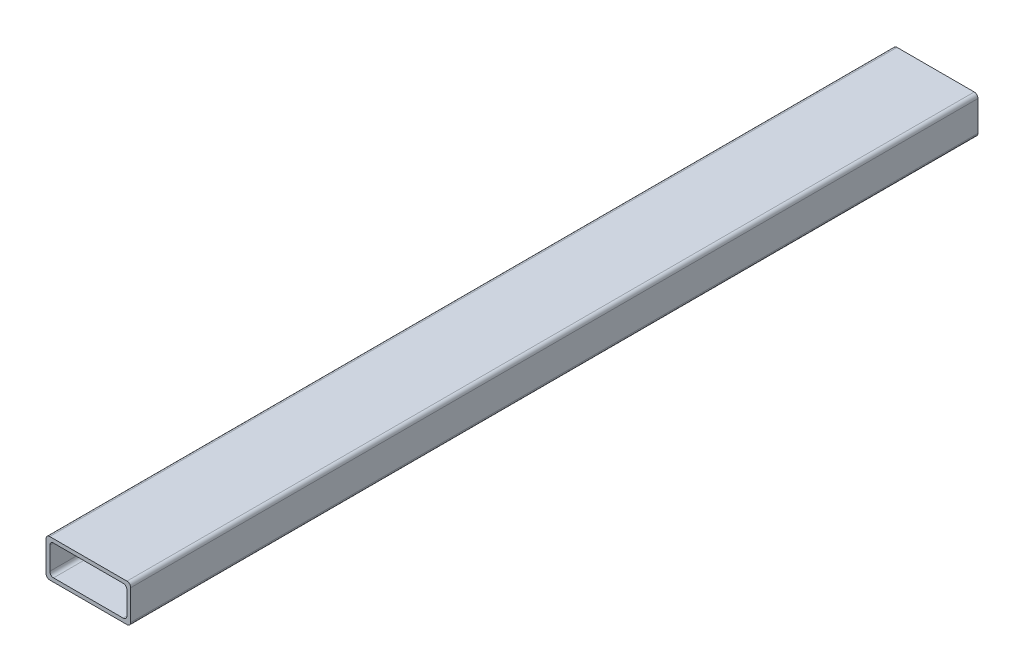
SolidWorks part; units mm, degrees
material "1.0490 (S275N)"
ref_plane "Front Plane" through (0, 0, 0) normal (0, 0, 1) x (1, 0, 0)
ref_plane "Top Plane" through (0, 0, 0) normal (0, 1, 0) x (1, 0, 0)
ref_plane "Right Plane" through (0, 0, 0) normal (1, 0, 0) x (0, 0, -1)
sketch "Sketch1" plane through (0, 0, 0) normal (0, 0, 1) x (1, 0, 0)
  line L0 (-67.0781, 7.7326) -> (-26.0781, 7.7326)
  line L1 (-69.0781, 9.7326) -> (-69.0781, 25.7326)
  line L2 (-67.0781, 27.7326) -> (-26.0781, 27.7326)
  line L3 (-24.0781, 25.7326) -> (-24.0781, 9.7326)
  line L4 (-26.0781, 23.7326) -> (-26.0781, 11.7326)
  line L5 (-65.0781, 9.7326) -> (-28.0781, 9.7326)
  line L6 (-67.0781, 11.7326) -> (-67.0781, 23.7326)
  line L7 (-65.0781, 25.7326) -> (-28.0781, 25.7326)
  line L8 (-67.0781, 25.7326) -> (-26.0781, 25.7326) construction
  line L9 (-67.0781, 9.7326) -> (-67.0781, 25.7326) construction
  line L10 (-26.0781, 25.7326) -> (-26.0781, 9.7326) construction
  line L11 (-67.0781, 9.7326) -> (-26.0781, 9.7326) construction
  line L12 (-69.0781, 27.7326) -> (-24.0781, 27.7326) construction
  line L13 (-69.0781, 7.7326) -> (-69.0781, 27.7326) construction
  line L14 (-24.0781, 27.7326) -> (-24.0781, 7.7326) construction
  line L15 (-69.0781, 7.7326) -> (-24.0781, 7.7326) construction
  arc A0 (-65.0781, 25.7326) -> (-67.0781, 23.7326) centre (-65.0781, 23.7326) ccw
  arc A1 (-26.0781, 23.7326) -> (-28.0781, 25.7326) centre (-28.0781, 23.7326) ccw
  arc A2 (-28.0781, 9.7326) -> (-26.0781, 11.7326) centre (-28.0781, 11.7326) ccw
  arc A3 (-67.0781, 11.7326) -> (-65.0781, 9.7326) centre (-65.0781, 11.7326) ccw
  arc A4 (-67.0781, 27.7326) -> (-69.0781, 25.7326) centre (-67.0781, 25.7326) ccw
  arc A5 (-24.0781, 25.7326) -> (-26.0781, 27.7326) centre (-26.0781, 25.7326) ccw
  arc A6 (-26.0781, 7.7326) -> (-24.0781, 9.7326) centre (-26.0781, 9.7326) ccw
  arc A7 (-69.0781, 9.7326) -> (-67.0781, 7.7326) centre (-67.0781, 9.7326) ccw
  dimension "D2" = 2
  dimension "D3" = 2
  dimension "D4" = 2
  dimension "D5" = 2
  dimension "D6" = 2
  dimension "D7" = 2
  dimension "D8" = 2
  dimension "D9" = 2
  dimension "D1" = 2
extrude "Boss-Extrude1" add sketch "Sketch1" along normal blind 450
